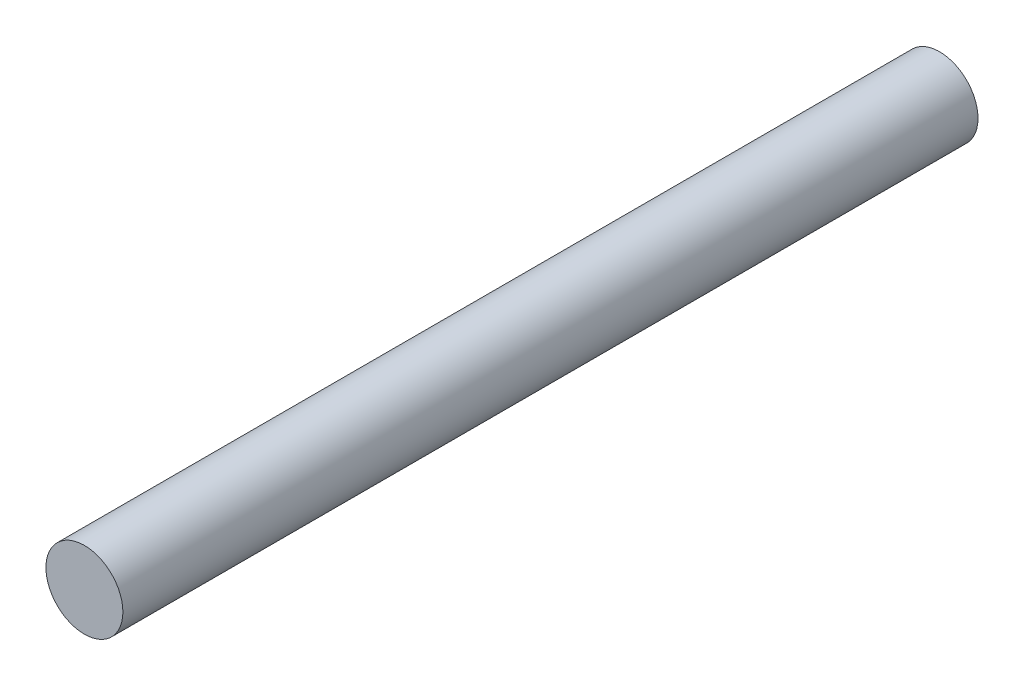
SolidWorks part; units mm, degrees
ref_plane "Front Plane" through (0, 0, 0) normal (0, 0, 1) x (1, 0, 0)
ref_plane "Top Plane" through (0, 0, 0) normal (0, 1, 0) x (1, 0, 0)
ref_plane "Right Plane" through (0, 0, 0) normal (1, 0, 0) x (0, 0, -1)
sketch "Sketch1" plane through (0, 0, 0) normal (0, 0, 1) x (1, 0, 0)
  circle A0 centre (0, 0) radius 1
  dimension "D1" = 2
extrude "Boss-Extrude1" add sketch "Sketch1" against normal blind 22.225
